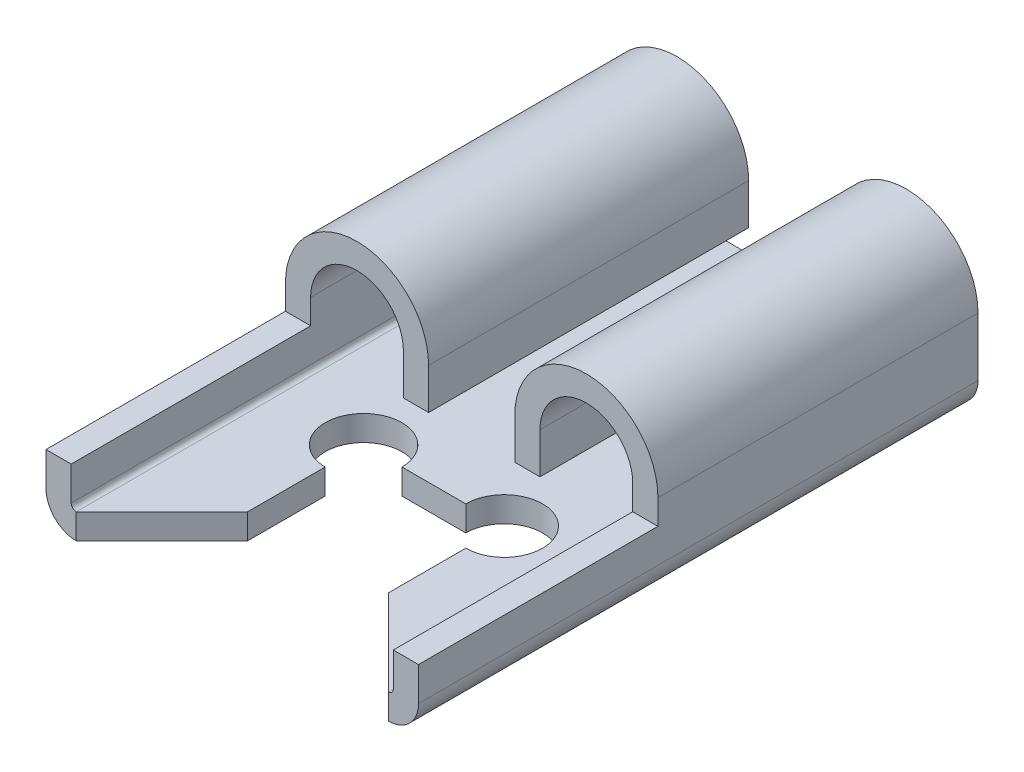
SolidWorks part; units mm, degrees
material "Duranickel(R) 301"
ref_plane "Front Plane" through (0, 0, 0) normal (0, 0, 1) x (1, 0, 0)
ref_plane "Top Plane" through (0, 0, 0) normal (0, 1, 0) x (1, 0, 0)
ref_plane "Right Plane" through (0, 0, 0) normal (1, 0, 0) x (0, 0, -1)
sketch "Sketch1" plane through (0, 0, 0) normal (0, 0, 1) x (1, 0, 0)
  line L0 (0, 0) -> (-3.095, 0)
  line L1 (-3.695, 0.6) -> (-3.695, 1.76)
  line L2 (-2.275, 3.18) -> (-6.9924, 3.18) construction
  line L3 (-0.855, 1.76) -> (-0.855, 0.95)
  line L4 (-2.275, 3.18) -> (-2.275, 0.5) construction
  line L5 (-1.355, 1.76) -> (-3.195, 1.76) construction
  line L6 (0, 0.5) -> (-3.095, 0.5)
  line L7 (-3.195, 0.6) -> (-3.195, 1.76)
  line L8 (-1.355, 1.76) -> (-1.355, 0.95)
  line L9 (-1.355, 0.95) -> (-0.855, 0.95)
  line L10 (0, 0) -> (0, 8.3351) construction
  line L11 (1.355, 1.76) -> (3.195, 1.76) construction
  line L12 (2.275, 3.18) -> (2.275, 0.5) construction
  line L13 (2.275, 3.18) -> (6.9924, 3.18) construction
  line L14 (1.355, 0.95) -> (0.855, 0.95)
  line L15 (1.355, 1.76) -> (1.355, 0.95)
  line L16 (3.195, 0.6) -> (3.195, 1.76)
  line L17 (0, 0.5) -> (3.095, 0.5)
  line L18 (0.855, 1.76) -> (0.855, 0.95)
  line L19 (3.695, 0.6) -> (3.695, 1.76)
  line L20 (0, 0) -> (3.095, 0)
  arc A0 (-0.855, 1.76) -> (-3.695, 1.76) centre (-2.275, 1.76) ccw
  arc A1 (-3.095, 0) -> (-3.695, 0.6) centre (-3.095, 0.6) cw
  arc A2 (-3.095, 0.5) -> (-3.195, 0.6) centre (-3.095, 0.6) cw
  arc A3 (-1.355, 1.76) -> (-3.195, 1.76) centre (-2.275, 1.76) ccw
  arc A4 (1.355, 1.76) -> (3.195, 1.76) centre (2.275, 1.76) cw
  arc A5 (3.095, 0.5) -> (3.195, 0.6) centre (3.095, 0.6) ccw
  arc A6 (3.095, 0) -> (3.695, 0.6) centre (3.095, 0.6) ccw
  arc A7 (0.855, 1.76) -> (3.695, 1.76) centre (2.275, 1.76) cw
  point P0 (3.695, 0)
  point P14 (-3.695, 0)
  dimension "D3" = 1.42
  dimension "D5" = 0.6
  dimension "D1" = 3.18
  dimension "D2" = 3.695
  dimension "D6" = 0.45
  dimension "D7" = 0.5
extrude "Boss-Extrude1" add sketch "Sketch1" against normal blind 11.1
sketch "Sketch2" plane through (0, 0, 0) normal (0, -1, 0) x (1, 0, 0)
  line L0 (-3.095, 0) -> (-1.395, -1.7)
  line L1 (-3.095, 0) -> (3.095, 0) construction
  line L2 (-1.395, -1.7) -> (-1.395, -3.238)
  line L3 (-0.633, -4) -> (0.633, -4)
  line L4 (0, 0) -> (0, -16.3705) construction
  line L5 (-3.095, 0) -> (-3.095, 0.5375)
  line L6 (-3.095, 0.5375) -> (3.095, 0.5375)
  line L7 (0, 0.5375) -> (0, -4) construction
  line L9 (3.095, 0) -> (3.095, 0.5375)
  line L10 (1.395, -1.7) -> (1.395, -3.238)
  line L11 (3.095, 0) -> (1.395, -1.7)
  arc A0 (-1.395, -3.238) -> (-0.633, -4) centre (-1.395, -4) ccw
  arc A1 (1.395, -3.238) -> (0.633, -4) centre (1.395, -4) cw
  dimension "D6" = 0.762
  dimension "D1" = 1.395
  dimension "D2" = 45
  dimension "D3" = 4
extrude "Cut-Extrude1" cut sketch "Sketch2" against normal up to next
sketch "Sketch3" plane through (0, 0, 0) normal (0, 0, 1) x (1, 0, 0)
  line L0 (3.695, 0.6) -> (3.695, 1.76) construction
  line L1 (-3.695, 3.3117) -> (3.695, 3.3117)
  line L2 (-3.695, 3.3117) -> (-3.695, 1.27)
  line L3 (-3.695, 1.27) -> (-3.095, 1.27)
  line L4 (3.695, 3.3117) -> (3.695, 1.27)
  line L5 (-3.695, 1.76) -> (-3.695, 0.6) construction
  line L7 (-3.095, 1.27) -> (-3.095, 0.77)
  line L8 (-3.095, 0.77) -> (3.095, 0.77)
  line L9 (3.095, 0.77) -> (3.095, 1.27)
  line L10 (3.095, 1.27) -> (3.695, 1.27)
  line L11 (-3.095, 0) -> (-1.395, 0) construction
  line L12 (-3.195, 0.6) -> (-3.195, 1.76) construction
  line L13 (3.195, 1.76) -> (3.195, 0.6) construction
  dimension "D1" = 1.27
  dimension "D2" = 0.5
  dimension "D3" = 0.1
  dimension "D4" = 0.1
extrude "Cut-Extrude2" cut sketch "Sketch3" against normal blind 4.75
